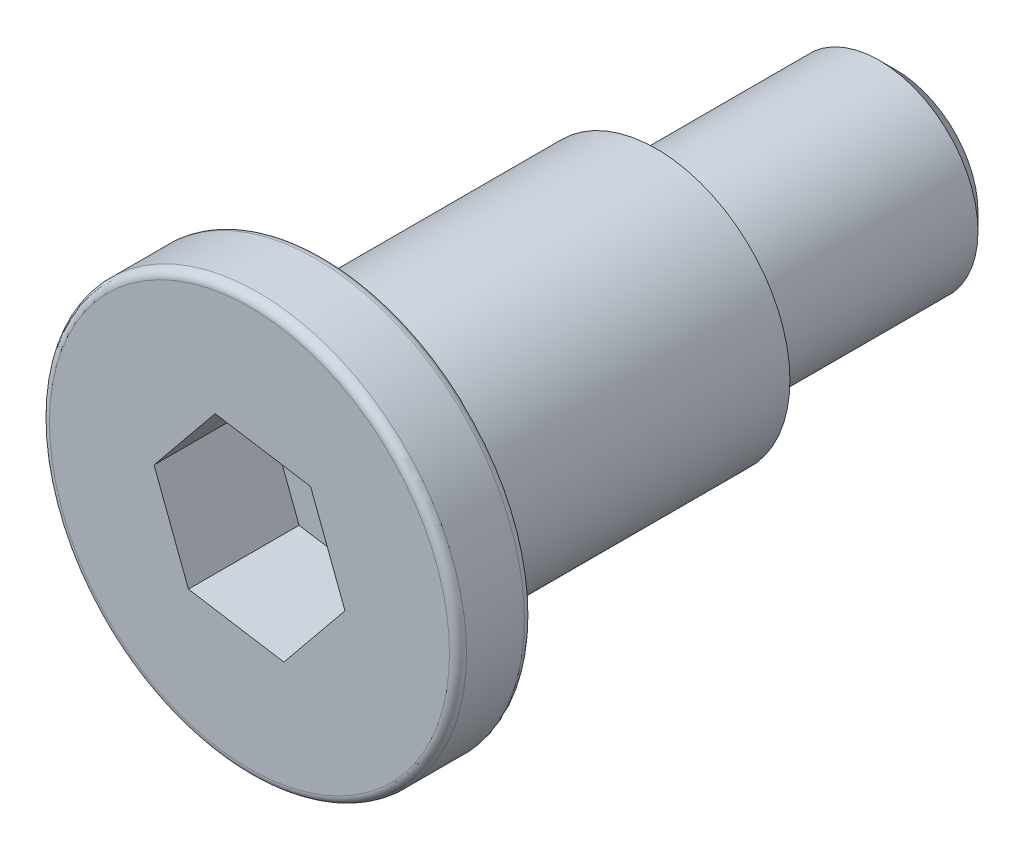
SolidWorks part; units mm, degrees
material "Stainless Steel (ferritic)"
ref_plane "Front Plane" through (0, 0, 0) normal (0, 0, 1) x (1, 0, 0)
ref_plane "Top Plane" through (0, 0, 0) normal (0, 1, 0) x (1, 0, 0)
ref_plane "Right Plane" through (0, 0, 0) normal (1, 0, 0) x (0, 0, -1)
sketch "Sketch1" plane through (0, 0, 0) normal (1, 0, 0) x (0, 0, -1)
  line L0 (0, 0) -> (9.652, 0)
  line L1 (9.652, 0) -> (9.652, 1.4732)
  line L2 (9.652, 1.4732) -> (6.0706, 1.4732)
  line L3 (6.0706, 1.4732) -> (6.0706, 1.9939)
  line L4 (6.0706, 1.9939) -> (1.1176, 1.9939)
  line L5 (1.1176, 1.9939) -> (1.1176, 3.1115)
  line L6 (1.1176, 3.1115) -> (0, 3.1115)
  line L7 (0, 3.1115) -> (0, 0)
  dimension "D1" = 9.652
  dimension "D2" = 1.1176
  dimension "D3" = 6.0706
  dimension "D4" = 1.4732
  dimension "D5" = 1.9939
  dimension "D6" = 3.1115
revolve "Revolve1" add sketch "Sketch1" angle 360 about L0
sketch "Sketch2" plane through (0, 0, 0) normal (0, 0, 1) x (1, 0, 0)
  line L1 (-0.9115, -1.1187) -> (0.513, -1.3487)
  line L2 (0.513, -1.3487) -> (1.4245, -0.2301)
  line L3 (1.4245, -0.2301) -> (0.9115, 1.1187)
  line L4 (0.9115, 1.1187) -> (-0.513, 1.3487)
  line L5 (-0.513, 1.3487) -> (-1.4245, 0.2301)
  line L6 (-1.4245, 0.2301) -> (-0.9115, -1.1187)
  circle A0 centre (0, 0) radius 1.2497 construction
extrude "Cut-Extrude1" cut sketch "Sketch2" against normal blind 1.651
fillet "Fillet1" radius 0.127 2 edges at (3.1115, 0, -1.1176) (3.1115, 0, 0)
chamfer "Chamfer1" distance 0.254 angle 45 1 edges at (1.4732, 0, -9.652)
scale "Scale1" scale about centroid uniform scaling yes scale factor 0.6
